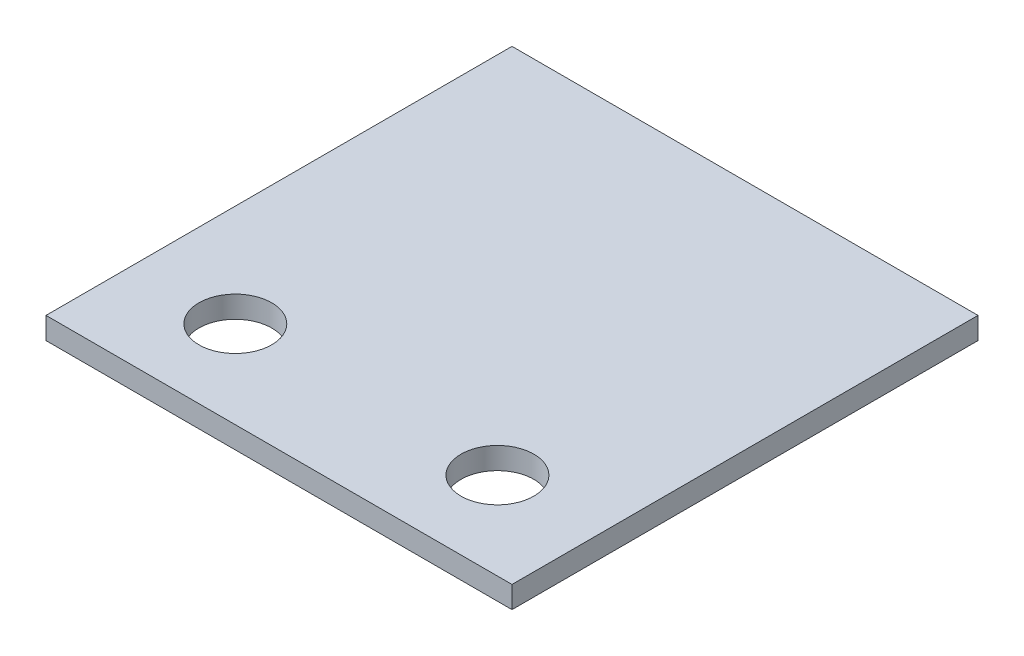
SolidWorks part; units mm, degrees
ref_plane "Front" through (0, 0, 0) normal (0, 0, 1) x (1, 0, 0)
ref_plane "Top" through (0, 0, 0) normal (0, 1, 0) x (1, 0, 0)
ref_plane "Right" through (0, 0, 0) normal (1, 0, 0) x (0, 0, -1)
sketch "草图1" plane through (0, 0, 0) normal (0, 1, 0) x (1, 0, 0)
  line L1 (-16, -16) -> (16, -16)
  line L2 (-16, -16) -> (-16, 16)
  line L3 (-16, 16) -> (16, 16)
  line L4 (16, -16) -> (16, 16)
  line L5 (-16, -16) -> (16, 16) construction
  line L6 (-16, 16) -> (16, -16) construction
  point P0 (0, 0)
extrude "凸台-拉伸1" add sketch "草图1" along normal blind 1.5
sketch "草图2" plane through (0, 1.5, 0) normal (0, 1, 0) x (1, 0, 0)
  circle A0 centre (9, -10) radius 2.5
extrude "切除-拉伸1" cut sketch "草图2" against normal through all
mirror "镜向1" about plane through (0, 0, 0) normal (1, 0, 0) of "切除-拉伸1"
